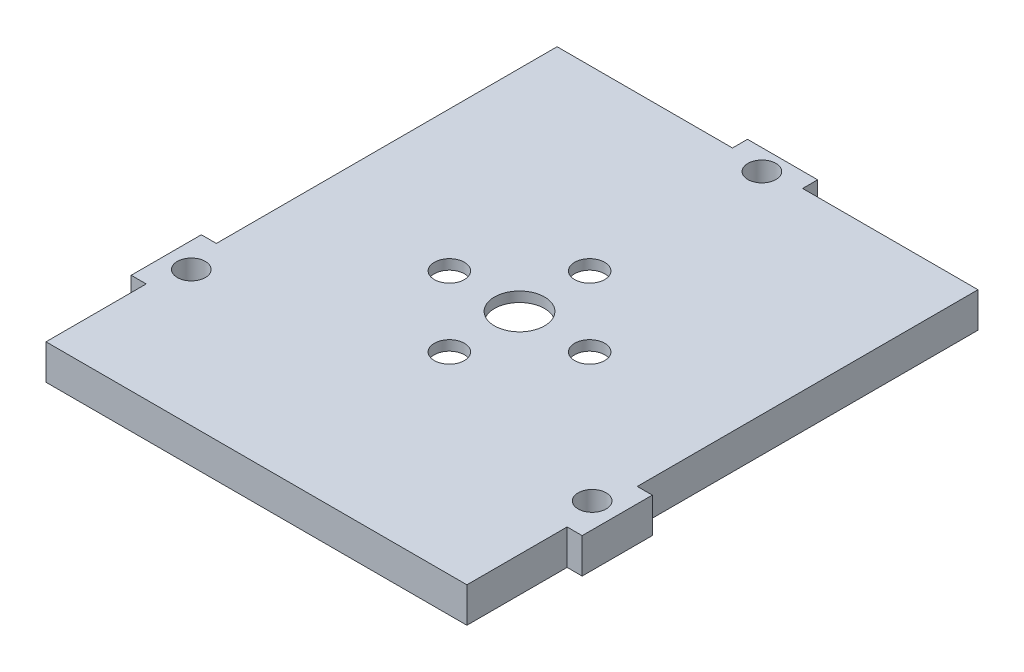
SolidWorks part; units mm, degrees
ref_plane "Front Plane" through (0, 0, 0) normal (0, 0, 1) x (1, 0, 0)
ref_plane "Top Plane" through (0, 0, 0) normal (0, 1, 0) x (1, 0, 0)
ref_plane "Right Plane" through (0, 0, 0) normal (1, 0, 0) x (0, 0, -1)
sketch "Sketch1" plane through (0, 0, 0) normal (0, 1, 0) x (1, 0, 0)
  line L1 (-21, 25.5) -> (21, 25.5)
  line L2 (-21, 25.5) -> (-21, -25.5)
  line L3 (-21, -25.5) -> (21, -25.5)
  line L4 (21, 25.5) -> (21, -25.5)
  point P4 (-21, 0)
  point P6 (0, 25.5)
  dimension "D1" = 42
  dimension "D2" = 51
extrude "Boss-Extrude1" add sketch "Sketch1" along normal blind 3.5
sketch "Sketch2" plane through (-21, 0, 0) normal (-1, 0, 0) x (0, 0, 1)
  line L0 (-25.5, 3.5) -> (25.5, 3.5) construction
  line L1 (15.5, 3.5) -> (8.5, 3.5)
  line L2 (15.5, 3.5) -> (15.5, 0)
  line L3 (15.5, 0) -> (8.5, 0)
  line L4 (8.5, 3.5) -> (8.5, 0)
  line L5 (-25.5, 0) -> (25.5, 0) construction
  line L6 (25.5, 3.5) -> (25.5, 0) construction
  dimension "D1" = 7
  dimension "D2" = 10
extrude "Boss-Extrude2" add sketch "Sketch2" along normal blind 1.5
sketch "Sketch3" plane through (21, 0, 0) normal (1, 0, 0) x (0, 0, -1)
  line L0 (25.5, 3.5) -> (-25.5, 3.5) construction
  line L1 (-8.5, 3.5) -> (-15.5, 3.5)
  line L2 (-8.5, 3.5) -> (-8.5, 0)
  line L3 (-8.5, 0) -> (-15.5, 0)
  line L4 (-15.5, 3.5) -> (-15.5, 0)
  line L5 (25.5, 0) -> (-25.5, 0) construction
  line L6 (-25.5, 3.5) -> (-25.5, 0) construction
  dimension "D1" = 7
  dimension "D2" = 10
extrude "Boss-Extrude3" add sketch "Sketch3" along normal blind 1.5
sketch "Sketch5" plane through (0, 0, -25.5) normal (0, 0, -1) x (-1, 0, 0)
  line L0 (21, 3.5) -> (-21, 3.5) construction
  line L1 (-3.5, 3.5) -> (3.5, 3.5)
  line L2 (-3.5, 3.5) -> (-3.5, 0)
  line L3 (-3.5, 0) -> (3.5, 0)
  line L4 (3.5, 3.5) -> (3.5, 0)
  line L5 (21, 0) -> (-21, 0) construction
  point P8 (0, 3.5)
  dimension "D1" = 7
extrude "Boss-Extrude4" add sketch "Sketch5" along normal blind 1.5
sketch "Sketch4" plane through (0, 3.5, 0) normal (0, 1, 0) x (1, 0, 0)
  line L0 (0, 16.7358) -> (0, -17.5419) construction
  line L1 (-22.5, -15.5) -> (-22.5, -8.5) construction
  line L2 (-3.5, 27) -> (3.5, 27) construction
  line L3 (-22.5, -12) -> (-17.5, -12) construction
  line L4 (-17.5, 22.875) -> (17.5, 22.875)
  line L5 (-17.5, 22.875) -> (-17.5, -22.875)
  line L6 (-17.5, -22.875) -> (17.5, -22.875)
  line L7 (17.5, 22.875) -> (17.5, -22.875)
  line L8 (0, 27) -> (0, 22.875) construction
  circle A0 centre (-20, -12) radius 1.4
  circle A1 centre (20, -12) radius 1.4
  circle A2 centre (0, 24.9375) radius 1.4
  point P9 (-22.5, -12)
  point P16 (0, 27)
  point P21 (-17.5, 0)
  point P22 (0, 22.875)
  point P25 (-20, -12)
  point P28 (0, 24.9375)
  dimension "D1" = 2.8
  dimension "D2" = 35
  dimension "D3" = 45.75
extrude "Cut-Extrude1" cut sketch "Sketch4" against normal blind 5 contours A0 | A1 | A2 | L5 L4 L7 L6
sketch "Sketch6" plane through (0, 3.5, 0) normal (0, 1, 0) x (1, 0, 0)
  line L0 (0, 7.75) -> (0, 0.75) construction
  line L1 (-7, 0.75) -> (0, 0.75) construction
  line L2 (-21, -25.5) -> (21, -25.5) construction
  line L4 (0, 27) -> (0, -25.5) construction
  line L5 (-3.5, 27) -> (3.5, 27) construction
  circle A0 centre (-7, 0.75) radius 1.5
  circle A1 centre (0, 7.75) radius 1.5
  circle A2 centre (7, 0.75) radius 1.5
  circle A3 centre (0, -6.25) radius 1.5
  circle A4 centre (0, 0.75) radius 2.5
  point P9 (0, 0.75)
  dimension "D1" = 3
  dimension "D5" = 5
  dimension "D2" = 7
extrude "Cut-Extrude2" cut sketch "Sketch6" against normal blind 2.5
sketch "Sketch7" plane through (0, 0, 0) normal (0, -1, 0) x (1, 0, 0)
  line L0 (-21, 25.5) -> (21, 25.5) construction
  line L1 (-12.5, 11.75) -> (12.5, 11.75)
  line L2 (-12.5, 11.75) -> (-12.5, -13.25)
  line L3 (-12.5, -13.25) -> (12.5, -13.25)
  line L4 (12.5, 11.75) -> (12.5, -13.25)
  line L6 (0, -27) -> (0, 25.5) construction
  line L7 (3.5, -27) -> (-3.5, -27) construction
  point P6 (0, 25.5)
  point P7 (0, 11.75)
  point P8 (0, -0.75)
  point P9 (12.5, -0.75)
  dimension "D1" = 25
  dimension "D2" = 25
extrude "Cut-Extrude3" cut sketch "Sketch7" against normal blind 2.5
